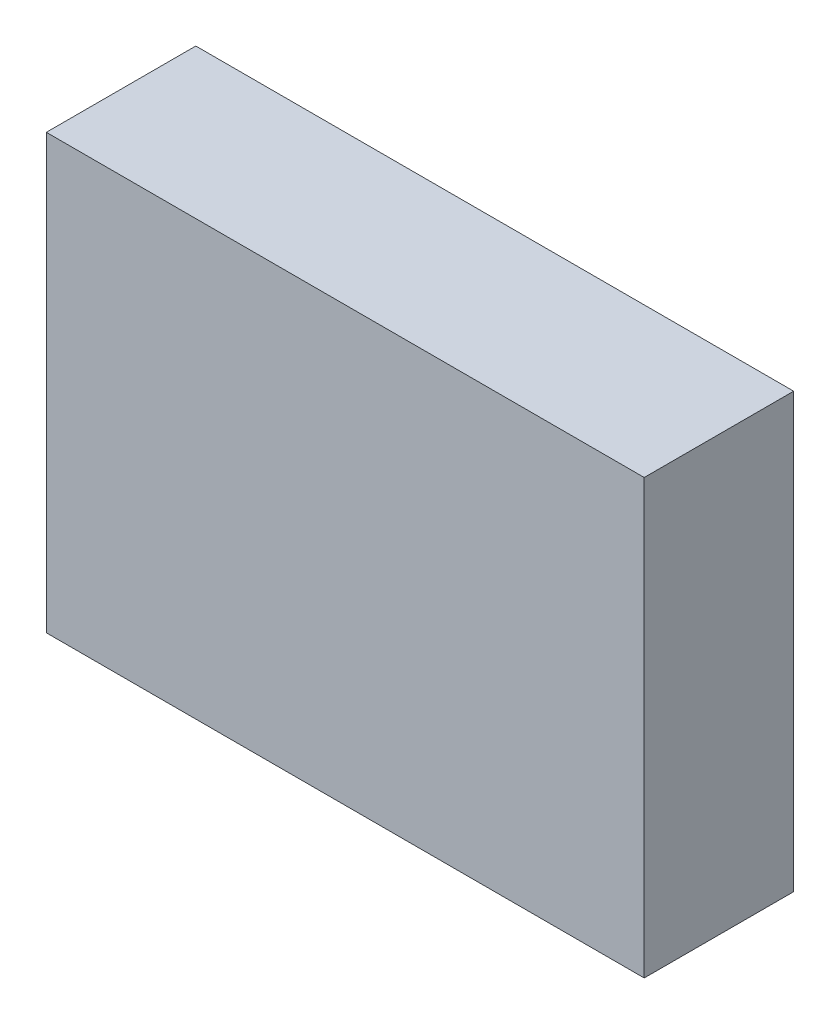
SolidWorks part; units mm, degrees
ref_plane "Front Plane" through (0, 0, 0) normal (0, 0, 1) x (1, 0, 0)
ref_plane "Top Plane" through (0, 0, 0) normal (0, 1, 0) x (1, 0, 0)
ref_plane "Right Plane" through (0, 0, 0) normal (1, 0, 0) x (0, 0, -1)
sketch "Sketch1" plane through (0, 0, 0) normal (0, 0, 1) x (1, 0, 0)
  line L1 (0, 0) -> (40, 0)
  line L2 (0, 0) -> (0, 29)
  line L3 (0, 29) -> (40, 29)
  line L4 (40, 0) -> (40, 29)
extrude "Boss-Extrude1" add sketch "Sketch1" against normal blind 10
